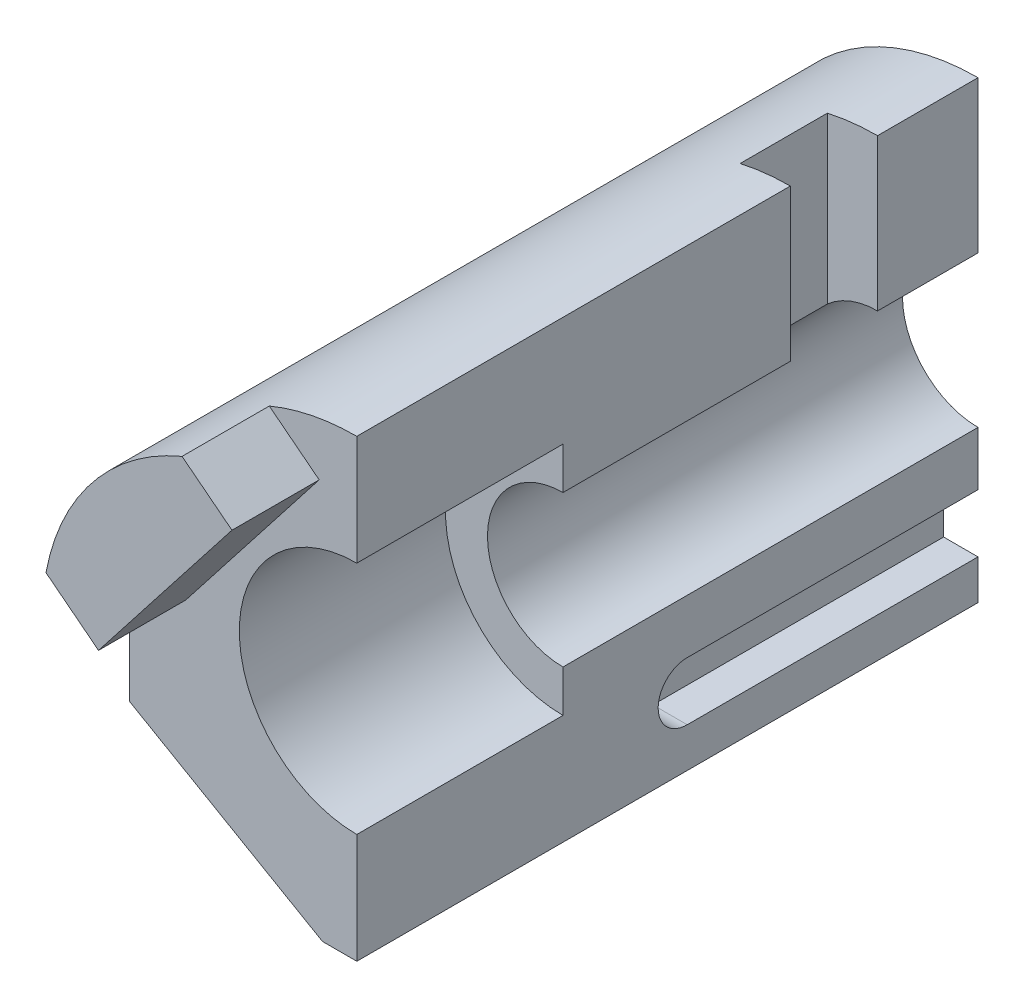
SolidWorks part; units mm, degrees
material "Alliage 1060"
ref_plane "Plan de face" through (0, 0, 0) normal (0, 0, 1) x (1, 0, 0)
ref_plane "Plan de dessus" through (0, 0, 0) normal (0, 1, 0) x (1, 0, 0)
ref_plane "Plan de droite" through (0, 0, 0) normal (1, 0, 0) x (0, 0, -1)
sketch "Esquisse1" plane through (0, 0, 0) normal (0, 0, 1) x (1, 0, 0)
  line L0 (0, -86) -> (0, 86)
  line L1 (0, -86) -> (-13, -86)
  line L5 (-86, 0) -> (-86, -43.8534)
  line L7 (-13, -86) -> (-86, -43.8534)
  arc A0 (0, 86) -> (-86, 0) centre (0, 0) ccw
  dimension "D1" = 172
  dimension "D2" = 13
extrude "Boss.-Extru.1" add sketch "Esquisse1" along normal blind 235
sketch "Esquisse2" plane through (0, 0, 235) normal (0, 0, 1) x (1, 0, 0)
  circle A0 centre (0, 0) radius 44.45
extrude "Enlèv. mat.-Extru.1" cut sketch "Esquisse2" against normal blind 78
sketch "Esquisse3" plane through (0, 0, 157) normal (0, 0, 1) x (1, 0, 0)
  line L0 (0, -44.45) -> (0, 44.45) construction
  circle A0 centre (0, 0) radius 28.575
extrude "Enlèv. mat.-Extru.2" cut sketch "Esquisse3" against normal through all
sketch "Esquisse7" plane through (0, 0, 235) normal (0, 0, 1) x (1, 0, 0)
  line L0 (0, 0) -> (-40.1885, 31.3987)
  line L1 (0, 0) -> (-155.8576, 0)
  line L2 (-14.2357, 64.6169) -> (-33.1164, 79.3681)
  line L3 (-64.7199, 0) -> (-14.2357, 64.6169)
  line L4 (-64.7199, 0) -> (-84.5876, 15.5223)
  arc A0 (0, 86) -> (-86, 0) centre (0, 0) ccw construction
  arc A1 (-33.1164, 79.3681) -> (-84.5876, 15.5223) centre (0, 0) ccw
  arc M5 (0, 86) -> (-86, 0) centre (0, 0) ccw
  dimension "D1" = 38
  dimension "D2" = 38
  dimension "D3" = 90
  dimension "D4" = 82
extrude "Boss.-Extru.4" add sketch "Esquisse7" along normal blind 33 contours L4 L3 L2 M5
sketch "Esquisse8" plane through (0, 0, 0) normal (1, 0, 0) x (0, 0, -1)
  line L0 (-71, 94.336) -> (-71, 4.336)
  line L3 (-71, 4.336) -> (-38, 4.336)
  line L4 (-38, 4.336) -> (-38, 94.336)
  line L5 (-38, 94.336) -> (-71, 94.336)
  line L6 (0, 28.575) -> (0, 86) construction
  dimension "D1" = 38
  dimension "D2" = 33
  dimension "D3" = 90
extrude "Enlèv. mat.-Extru.4" cut sketch "Esquisse8" against normal blind 19 contours L5 L0 L3 L4
sketch "Esquisse9" plane through (0, 0, 0) normal (1, 0, 0) x (0, 0, -1)
  line L0 (0, -60) -> (-110, -60)
  line L1 (0, -86) -> (0, -28.575) construction
  line L2 (-235, -86) -> (0, -86) construction
  line L3 (-110, -49) -> (0, -49)
  line L4 (-110, -71) -> (0, -71)
  line L5 (0, -71) -> (0, -49)
  arc A0 (-110, -49) -> (-110, -71) centre (-110, -60) ccw
  dimension "D1" = 26
  dimension "D2" = 110
extrude "Enlèv. mat.-Extru.5" cut sketch "Esquisse9" against normal blind 13
sketch "Esquisse4" plane through (0, 0, 235) normal (0, 0, 1) x (1, 0, 0)
  line L1 (-13, 86) -> (-114.9095, -19.0921)
  line L2 (-114.9095, -19.0921) -> (-114.9095, 86)
  line L3 (-114.9095, 86) -> (-13, 86)
  line L7 (-13, 86) -> (-13, -81.662)
  line L8 (-13, -81.662) -> (-0.0929, -81.662)
  line L9 (-0.0929, -81.662) -> (0, 86)
  line L10 (0, -86) -> (0, -44.45) construction
  line L11 (0, 86) -> (-13, 86)
  arc A1 (0, 86) -> (-65.567, -55.6504) centre (0, 0) ccw construction
  dimension "D1" = 13
equation "\"A\"= 235"
equation "\"B\"= 110"
equation "\"C\"= 86"
equation "\"D1@Esquisse1\"=\"C\"*2"
equation "\"D1@Boss.-Extru.1\"=\"A\""
